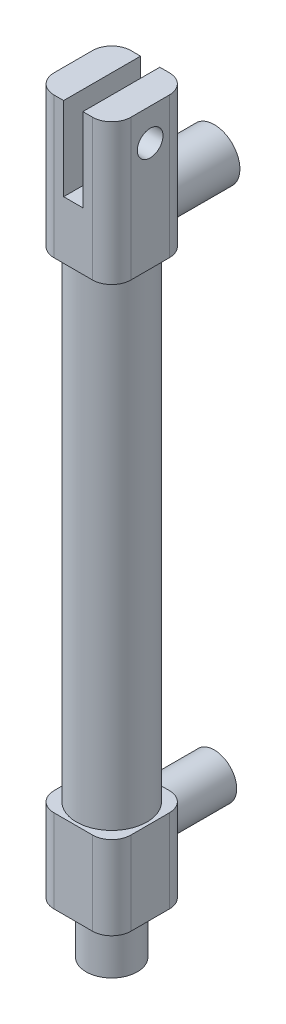
SolidWorks part; units mm, degrees
ref_plane "Front Plane" through (0, 0, 0) normal (0, 0, 1) x (1, 0, 0)
ref_plane "Top Plane" through (0, 0, 0) normal (0, 1, 0) x (1, 0, 0)
ref_plane "Right Plane" through (0, 0, 0) normal (1, 0, 0) x (0, 0, -1)
sketch "Sketch1" plane through (0, 0, 0) normal (0, 1, 0) x (1, 0, 0)
  circle A0 centre (-60.0596, 11.2493) radius 5.5
extrude "Boss-Extrude1" add sketch "Sketch1" along normal blind 75
sketch "Sketch2" plane through (0, 75, 0) normal (0, 1, 0) x (1, 0, 0)
  line L1 (-63.0596, 17.2493) -> (-57.0596, 17.2493)
  line L2 (-66.0596, 14.2493) -> (-66.0596, 8.2493)
  line L3 (-63.0596, 5.2493) -> (-57.0596, 5.2493)
  line L4 (-54.0596, 14.2493) -> (-54.0596, 8.2493)
  line L5 (-66.0596, 17.2493) -> (-54.0596, 5.2493) construction
  line L6 (-66.0596, 5.2493) -> (-54.0596, 17.2493) construction
  arc A0 (-54.0596, 8.2493) -> (-57.0596, 5.2493) centre (-57.0596, 8.2493) cw
  arc A1 (-63.0596, 5.2493) -> (-66.0596, 8.2493) centre (-63.0596, 8.2493) cw
  arc A2 (-63.0596, 17.2493) -> (-66.0596, 14.2493) centre (-63.0596, 14.2493) ccw
  arc A3 (-57.0596, 17.2493) -> (-54.0596, 14.2493) centre (-57.0596, 14.2493) cw
  point P0 (-60.0596, 11.2493)
  dimension "D2" = 3
  dimension "D1" = 12
extrude "Boss-Extrude2" add sketch "Sketch2" along normal blind 22
sketch "Sketch3" plane through (-66.0596, 0, 0) normal (-1, 0, 0) x (0, 0, 1)
  line L0 (-14.2493, 97) -> (-8.2493, 97) construction
  circle A0 centre (-11.2493, 92) radius 2
  dimension "D1" = 5
extrude "Cut-Extrude1" cut sketch "Sketch3" against normal through all
sketch "Sketch4" plane through (0, 97, 0) normal (0, 1, 0) x (1, 0, 0)
  line L0 (-63.0596, 5.2493) -> (-57.0596, 5.2493) construction
  line L1 (-61.5596, 17.2493) -> (-58.5596, 17.2493)
  line L2 (-61.5596, 17.2493) -> (-61.5596, 5.2493)
  line L3 (-61.5596, 5.2493) -> (-58.5596, 5.2493)
  line L4 (-58.5596, 17.2493) -> (-58.5596, 5.2493)
  line L5 (-61.5596, 17.2493) -> (-58.5596, 5.2493) construction
  line L6 (-61.5596, 5.2493) -> (-58.5596, 17.2493) construction
  point P0 (-60.0596, 11.2493)
  dimension "D1" = 1.5
extrude "Cut-Extrude2" cut sketch "Sketch4" against normal blind 13
sketch "Sketch5" plane through (0, 0, -17.2493) normal (0, 0, -1) x (-1, 0, 0)
  line L0 (54.5596, 75) -> (65.5596, 75) construction
  circle A0 centre (60.0596, 79.5) radius 4
  dimension "D1" = 4.5
extrude "Boss-Extrude3" add sketch "Sketch5" along normal blind 10
sketch "Sketch6" plane through (0, 0, 0) normal (0, -1, 0) x (1, 0, 0)
  line L1 (-57.0596, -17.2493) -> (-63.0596, -17.2493)
  line L2 (-54.0596, -14.2493) -> (-54.0596, -8.2493)
  line L3 (-57.0596, -5.2493) -> (-63.0596, -5.2493)
  line L4 (-66.0596, -14.2493) -> (-66.0596, -8.2493)
  line L5 (-54.0596, -17.2493) -> (-66.0596, -5.2493) construction
  line L6 (-54.0596, -5.2493) -> (-66.0596, -17.2493) construction
  arc A0 (-57.0596, -5.2493) -> (-54.0596, -8.2493) centre (-57.0596, -8.2493) cw
  arc A1 (-63.0596, -5.2493) -> (-66.0596, -8.2493) centre (-63.0596, -8.2493) ccw
  arc A2 (-66.0596, -14.2493) -> (-63.0596, -17.2493) centre (-63.0596, -14.2493) ccw
  arc A3 (-54.0596, -14.2493) -> (-57.0596, -17.2493) centre (-57.0596, -14.2493) cw
  point P0 (-60.0596, -11.2493)
  dimension "D3" = 3
  dimension "D1" = 12
  dimension "D2" = 12
extrude "Boss-Extrude4" add sketch "Sketch6" along normal blind 13
sketch "Sketch7" plane through (0, 0, -17.2493) normal (0, 0, -1) x (-1, 0, 0)
  line L0 (63.0596, 0) -> (57.0596, 0) construction
  circle A0 centre (60.0596, -4.5) radius 3.5
  dimension "D1" = 4.5
extrude "Boss-Extrude5" add sketch "Sketch7" along normal blind 10
sketch "Sketch9" plane through (0, -13, 0) normal (0, -1, 0) x (1, 0, 0)
  circle A0 centre (-60.0596, -11.2493) radius 4
extrude "Boss-Extrude6" add sketch "Sketch9" along normal blind 8
sketch "Sketch10" plane through (0, -21, 0) normal (0, -1, 0) x (1, 0, 0)
  circle A0 centre (-60.0596, -11.2493) radius 2
extrude "Cut-Extrude3" cut sketch "Sketch10" against normal blind 80
